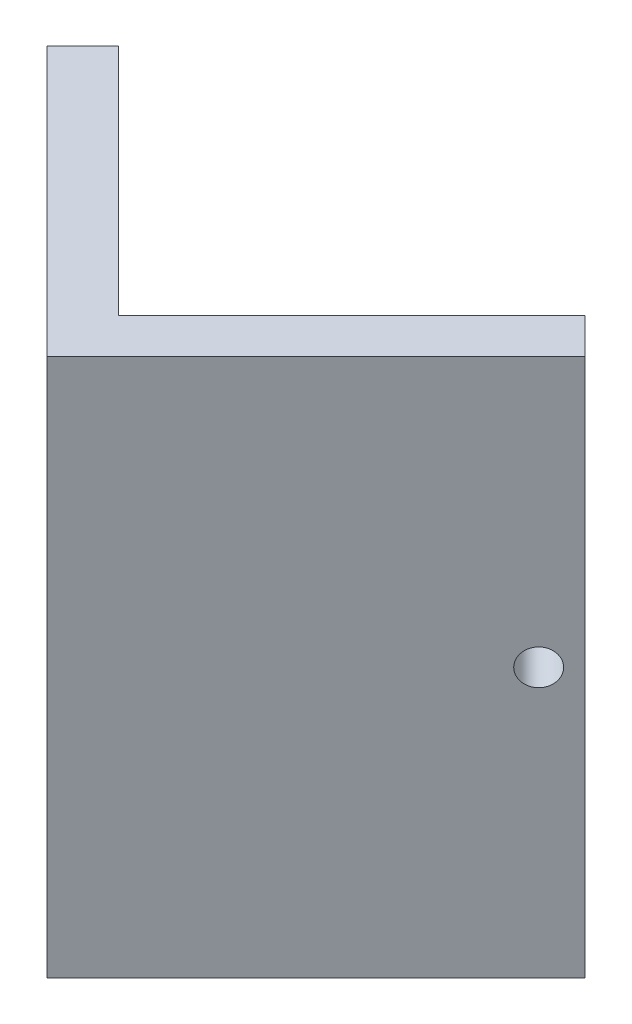
SolidWorks part; units mm, degrees
ref_plane "Front Plane" through (0, 0, 0) normal (0, 0, 1) x (1, 0, 0)
ref_plane "Top Plane" through (0, 0, 0) normal (0, 1, 0) x (1, 0, 0)
ref_plane "Right Plane" through (0, 0, 0) normal (1, 0, 0) x (0, 0, -1)
sketch "Sketch1" plane through (0, 0, 0) normal (0, 1, 0) x (1, 0, 0)
  line L0 (0, 0) -> (13.8787, 13.8787)
  line L1 (0, 0) -> (-13.8787, 13.8787)
  line L2 (-13.8787, 13.8787) -> (-16, 11.7574)
  line L3 (13.8787, 13.8787) -> (16, 11.7574)
  line L4 (0, 0) -> (0, 36.4866)
  line L5 (-16, 11.7574) -> (0, -4.2426)
  line L6 (0, -4.2426) -> (16, 11.7574)
  line L7 (-13.1716, 13.1716) -> (-2.9185, 23.4246) construction
  line L8 (-2.9185, 23.4246) -> (-1.575, 22.0811) construction
  line L9 (-1.575, 22.0811) -> (-11.8281, 11.8281) construction
  line L10 (13.1716, 13.1716) -> (2.9185, 23.4246) construction
  line L11 (2.9185, 23.4246) -> (1.575, 22.0811) construction
  line L12 (1.575, 22.0811) -> (11.8281, 11.8281) construction
  line L13 (-13.8787, 13.8787) -> (-13.1716, 13.1716)
  line L14 (-13.8787, 13.8787) -> (-11.865, 15.8924) construction
  line L15 (-11.865, 15.8924) -> (-11.1578, 15.1853) construction
  line L16 (13.8787, 13.8787) -> (11.865, 15.8924) construction
  line L17 (11.865, 15.8924) -> (11.1578, 15.1853) construction
  point P14 (-2.9945, 21.9344)
  point P21 (-2.894, 22.035)
  dimension "D1" = 45
  dimension "D2" = 45
  dimension "D3" = 32
  dimension "D4" = 3
  dimension "D5" = 1
  dimension "D6" = 1.9
extrude "Boss-Extrude1" add sketch "Sketch1" along normal blind 32 contours L5 L6 L3 L0 L1 L2
sketch "Sketch2" plane through (0, 0, 0) normal (0.7071, 0, -0.7071) x (-0.7071, 0, -0.7071)
  line L0 (19.6274, 16) -> (17.6774, 16)
  line L1 (19.6274, 32) -> (19.6274, 0) construction
  circle A0 centre (17.6774, 16) radius 1.05
  dimension "D2" = 2.1
  dimension "D1" = 1.95
extrude "Cut-Extrude1" cut sketch "Sketch2" against normal blind 32
sketch "Sketch3" plane through (0, 0, 0) normal (-0.7071, 0, -0.7071) x (-0.7071, 0, 0.7071)
  line L0 (-19.6274, 16) -> (-17.6774, 16)
  line L1 (-19.6274, 32) -> (-19.6274, 0) construction
  circle A0 centre (-17.6774, 16) radius 1.05
  dimension "D1" = 2.1
  dimension "D2" = 1.95
extrude "Cut-Extrude2" cut sketch "Sketch3" against normal blind 32
